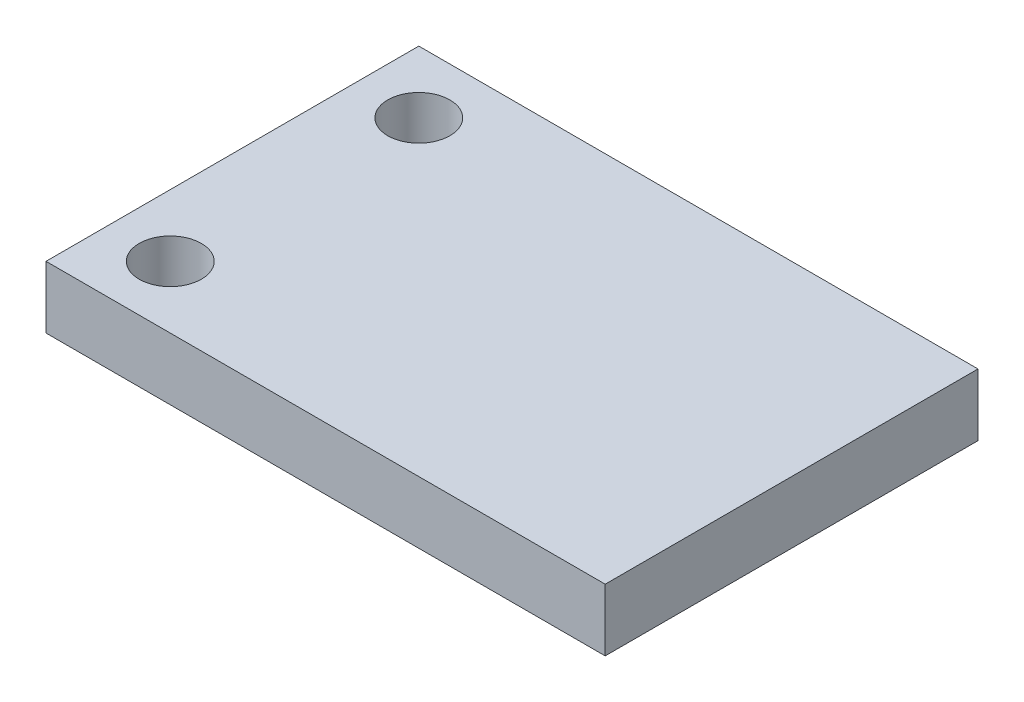
SolidWorks part; units mm, degrees
ref_plane "Płaszczyzna przednia" through (0, 0, 0) normal (0, 0, 1) x (1, 0, 0)
ref_plane "Płaszczyzna górna" through (0, 0, 0) normal (0, 1, 0) x (1, 0, 0)
ref_plane "Płaszczyzna prawa" through (0, 0, 0) normal (1, 0, 0) x (0, 0, -1)
sketch "Szkic1" plane through (0, 0, 0) normal (0, 1, 0) x (1, 0, 0)
  line L1 (0, 0) -> (90, 0)
  line L2 (0, 0) -> (0, 60)
  line L3 (0, 60) -> (90, 60)
  line L4 (90, 0) -> (90, 60)
  circle A0 centre (10, 50) radius 5
  circle A1 centre (10, 10) radius 5
  dimension "D3" = 10
  dimension "D4" = 10
  dimension "D5" = 10
  dimension "D1" = 90
  dimension "D2" = 60
  dimension "D6" = 2
extrude "Dodanie-wyciągnięcie1" add sketch "Szkic1" along normal blind 10
